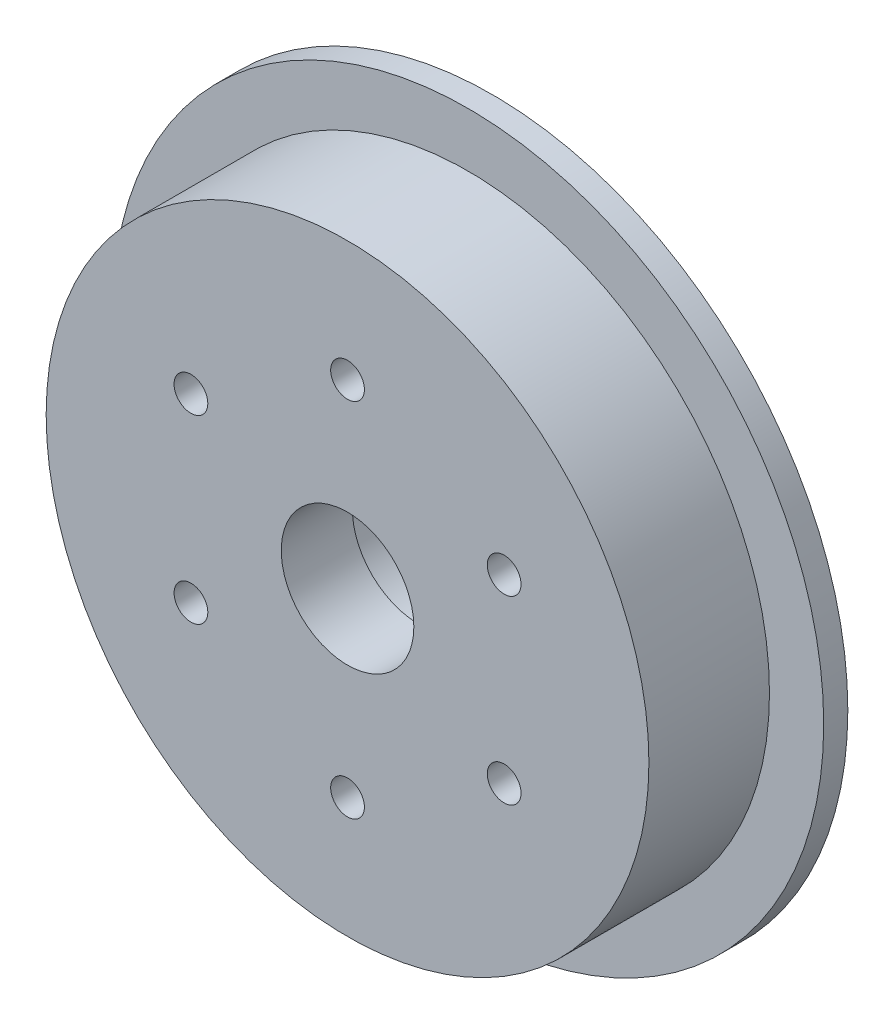
SolidWorks part; units mm, degrees
material "聚脂树脂"
ref_plane "前视基准面" through (0, 0, 0) normal (0, 0, 1) x (1, 0, 0)
ref_plane "上视基准面" through (0, 0, 0) normal (0, 1, 0) x (1, 0, 0)
ref_plane "右视基准面" through (0, 0, 0) normal (1, 0, 0) x (0, 0, -1)
sketch "草图2" plane through (0, 0, 0) normal (0, 0, 1) x (1, 0, 0)
  circle A0 centre (0, 0) radius 29.5
  dimension "D1" = 59
extrude "凸台-拉伸1" add sketch "草图2" along normal blind 2
sketch "草图3" plane through (0, 0, 2) normal (0, 0, 1) x (1, 0, 0)
  circle A0 centre (0, 0) radius 25
  dimension "D1" = 50
extrude "凸台-拉伸2" add sketch "草图3" along normal blind 10
sketch "草图7" plane through (0, 0, 12) normal (0, 0, 1) x (1, 0, 0)
  line L0 (0, 0) -> (12.9904, 7.5)
  line L1 (0, 0) -> (17, 0)
  circle A0 centre (12.9904, 7.5) radius 1.4
  circle A2 centre (12.9904, -7.5) radius 1.4
  circle A3 centre (0, -15) radius 1.4
  circle A4 centre (-12.9904, -7.5) radius 1.4
  circle A5 centre (-12.9904, 7.5) radius 1.4
  circle A6 centre (0, 15) radius 1.4
  point P18 (0, 0)
  dimension "D4" = 2.8
  dimension "D1" = 30
  dimension "D2" = 15
  dimension "D3" = 6
extrude "切除-拉伸3" cut sketch "草图7" against normal blind 12
sketch "草图9" plane through (0, 0, 0) normal (0, 0, -1) x (-1, 0, 0)
  circle A0 centre (0, 0) radius 6.5
  dimension "D1" = 13
extrude "切除-拉伸4" cut sketch "草图9" against normal up to next
sketch "草图10" plane through (0, 0, 12) normal (0, 0, 1) x (1, 0, 0)
  circle A0 centre (0, 0) radius 5.5
  circle A1 centre (0, 0) radius 6.5 construction
  circle A2 centre (0, 0) radius 6.5
  dimension "D1" = 11
extrude "凸台-拉伸4" add sketch "草图10" against normal blind 5.9
